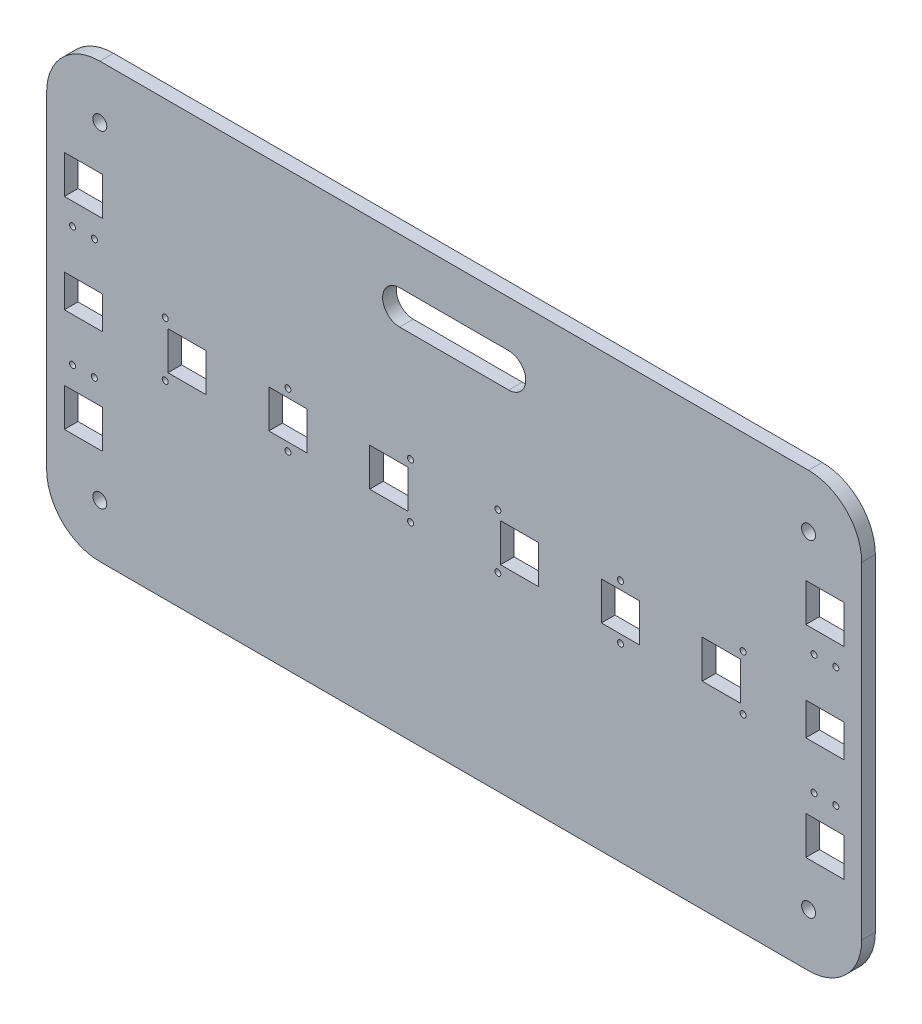
SolidWorks part; units mm, degrees
material "玻璃"
ref_plane "前视基准面" through (0, 0, 0) normal (0, 0, 1) x (1, 0, 0)
ref_plane "上视基准面" through (0, 0, 0) normal (0, 1, 0) x (1, 0, 0)
ref_plane "右视基准面" through (0, 0, 0) normal (1, 0, 0) x (0, 0, -1)
sketch "草图2" plane through (0, 0, 0) normal (0, 0, 1) x (1, 0, 0)
  line L0 (0, 1004.6496) -> (0, 0) construction
  line L10 (-68, -43) -> (-68, -57)
  line L11 (-31, -43) -> (-17, -43)
  line L19 (-22.1829, -50) -> (7.7078, -50) construction
  line L24 (31, -57) -> (17, -57)
  line L29 (17, -43) -> (17, -57)
  line L46 (129, -80) -> (143, -80)
  line L47 (-130, -130) -> (130, -130) construction
  line L48 (-150, -110) -> (-150, 10) construction
  line L49 (-130, 30) -> (130, 30) construction
  line L50 (150, -110) -> (150, 10) construction
  line L51 (0, 30) -> (0, 0) construction
  line L52 (-150, -50) -> (150, -50) construction
  line L53 (129, -6) -> (143, -6)
  line L58 (129, -6) -> (129, -20)
  line L59 (129, -20) -> (143, -20)
  line L60 (143, -6) -> (143, -20)
  line L65 (28.2222, 0) -> (37.5982, 0) construction
  line L66 (0, 0) -> (0, -130) construction
  line L71 (-130, 29.5) -> (130, 29.5)
  line L72 (-20, 12.5) -> (20, 12.5)
  line L73 (0, 0) -> (0, -1009.2088) construction
  line L74 (136, -20) -> (136, -6) construction
  line L75 (129, -13) -> (143, -13) construction
  line L76 (143, -94) -> (143, -80)
  line L77 (129, -94) -> (143, -94)
  line L78 (129, -94) -> (129, -80)
  line L79 (-129, -94) -> (-129, -80)
  line L80 (-129, -94) -> (-143, -94)
  line L81 (-143, -94) -> (-143, -80)
  line L82 (-129, -80) -> (-143, -80)
  line L83 (-129, -20) -> (-143, -20)
  line L84 (-143, -6) -> (-143, -20)
  line L85 (-129, -6) -> (-143, -6)
  line L86 (-129, -6) -> (-129, -20)
  line L87 (-31, -43) -> (-31, -57)
  line L88 (-31, -57) -> (-17, -57)
  line L89 (-17, -43) -> (-17, -57)
  line L90 (-24, -57) -> (-24, -43) construction
  line L91 (-31, -50) -> (-17, -50) construction
  line L92 (-68, -43) -> (-54, -43)
  line L93 (-54, -43) -> (-54, -57)
  line L94 (-68, -57) -> (-54, -57)
  line L95 (-105, -43) -> (-105, -57)
  line L96 (-105, -43) -> (-91, -43)
  line L97 (-91, -43) -> (-91, -57)
  line L98 (-105, -57) -> (-91, -57)
  line L99 (31, -43) -> (17, -43)
  line L100 (31, -43) -> (31, -57)
  line L101 (68, -43) -> (54, -43)
  line L102 (54, -43) -> (54, -57)
  line L103 (68, -57) -> (54, -57)
  line L104 (68, -43) -> (68, -57)
  line L105 (105, -43) -> (91, -43)
  line L106 (91, -43) -> (91, -57)
  line L107 (105, -57) -> (91, -57)
  line L108 (105, -43) -> (105, -57)
  line L109 (-31, -43) -> (-68, -43) construction
  line L110 (-61, -43) -> (-61, -57) construction
  line L112 (-111, -35) -> (-11, -35) construction
  line L113 (-111, -35) -> (-111, -65) construction
  line L114 (-111, -65) -> (-11, -65) construction
  line L115 (-11, -35) -> (-11, -65) construction
  line L116 (-61, -65) -> (-61, -35) construction
  line L117 (-111, -50) -> (-11, -50) construction
  line L121 (-106, -40) -> (-16, -40) construction
  line L122 (-16, -40) -> (-16, -60) construction
  line L123 (-106, -60) -> (-16, -60) construction
  line L124 (-106, -40) -> (-106, -60) construction
  line L125 (136, -20) -> (136, -42.3074) construction
  line L126 (-20, 12.5) -> (-20, 0) construction
  line L127 (128, -4) -> (144, -4) construction
  line L128 (128, -4) -> (128, -96) construction
  line L129 (128, -96) -> (144, -96) construction
  line L130 (144, -4) -> (144, -96) construction
  line L131 (136, -96) -> (136, -4) construction
  line L132 (128, -50) -> (144, -50) construction
  line L133 (132, -28) -> (140, -28) construction
  line L134 (132, -28) -> (132, -72) construction
  line L135 (132, -72) -> (140, -72) construction
  line L136 (140, -28) -> (140, -72) construction
  line L137 (136, -72) -> (136, -28) construction
  line L138 (132, -50) -> (140, -50) construction
  line L139 (-20, 0) -> (20, 0)
  line L140 (20, 12.5) -> (20, 0) construction
  line L141 (0, 0) -> (0, 12.5) construction
  line L142 (-20, 6.25) -> (20, 6.25) construction
  line L143 (149.5, -110) -> (149.5, 10)
  line L144 (-130, -129.5) -> (130, -129.5)
  line L145 (-149.5, -110) -> (-149.5, 10)
  line L146 (-129, -56) -> (-143, -56)
  line L147 (129, -44) -> (143, -44)
  line L148 (129, -44) -> (129, -56)
  line L149 (129, -56) -> (143, -56)
  line L150 (143, -44) -> (143, -56)
  line L151 (136, -56) -> (136, -44) construction
  line L152 (129, -50) -> (143, -50) construction
  line L153 (-143, -44) -> (-143, -56)
  line L154 (-129, -44) -> (-143, -44)
  line L155 (-129, -44) -> (-129, -56)
  arc A0 (130, 30) -> (150, 10) centre (130, 10) cw construction
  arc A1 (150, -110) -> (130, -130) centre (130, -110) cw construction
  arc A2 (-130, -130) -> (-150, -110) centre (-130, -110) cw construction
  arc A3 (-150, 10) -> (-130, 30) centre (-130, 10) cw construction
  circle A5 centre (130, -110) radius 2.55
  circle A6 centre (130, 10) radius 2.55
  circle A7 centre (-130, -110) radius 2.55
  circle A8 centre (-130, 10) radius 2.55
  circle A13 centre (-106, -40) radius 1.1
  circle A14 centre (-106, -60) radius 1.1
  circle A15 centre (-16, -40) radius 1.1
  circle A16 centre (-16, -60) radius 1.1
  circle A17 centre (-61, -60) radius 1.1
  circle A18 centre (-61, -40) radius 1.1
  circle A19 centre (16, -60) radius 1.1
  circle A20 centre (16, -40) radius 1.1
  circle A21 centre (61, -60) radius 1.1
  circle A22 centre (61, -40) radius 1.1
  circle A23 centre (106, -60) radius 1.1
  circle A24 centre (106, -40) radius 1.1
  circle A25 centre (140, -28) radius 1.1
  circle A26 centre (132, -28) radius 1.1
  circle A27 centre (132, -72) radius 1.1
  circle A28 centre (140, -72) radius 1.1
  circle A29 centre (-140, -72) radius 1.1
  circle A30 centre (-132, -72) radius 1.1
  circle A31 centre (-132, -28) radius 1.1
  circle A32 centre (-140, -28) radius 1.1
  arc A33 (-20, 12.5) -> (-20, 0) centre (-20, 6.25) ccw
  arc A34 (20, 0) -> (20, 12.5) centre (20, 6.25) ccw
  arc A35 (130, 29.5) -> (149.5, 10) centre (130, 10) cw
  arc A36 (149.5, -110) -> (130, -129.5) centre (130, -110) cw
  arc A37 (-130, -129.5) -> (-149.5, -110) centre (-130, -110) cw
  arc A38 (-149.5, 10) -> (-130, 29.5) centre (-130, 10) cw
  point P0 (0, 0)
  point P1 (0, 0)
  point P4 (-24, -50)
  point P36 (-61, -50)
  point P38 (0, -50)
  point P39 (-61, -50)
  point P40 (0, -50)
  point P41 (136, -13)
  point P51 (136, -50)
  point P53 (136, -50)
  point P54 (136, -50)
  point P61 (150, 30)
  point P64 (150, -130)
  point P70 (-150, 30)
  point P102 (-61, -40)
  point P103 (-61, -60)
  point P142 (136, -50)
  point P145 (0, 6.25)
  dimension "D15" = 20
  dimension "D16" = 5.1
  dimension "D17" = 5.1
  dimension "D18" = 5.1
  dimension "D19" = 5.1
  dimension "D20" = 30
  dimension "D25" = 2.2
  dimension "D26" = 2.2
  dimension "D27" = 2.2
  dimension "D28" = 2.2
  dimension "D29" = 2.2
  dimension "D30" = 2.2
  dimension "D35" = 2.2
  dimension "D36" = 2.2
  dimension "D37" = 2.2
  dimension "D38" = 2.2
  dimension "D3" = 14
  dimension "D4" = 14
  dimension "D5" = 17
  dimension "D6" = 40
  dimension "D7" = 12.5
  dimension "D8" = 3
  dimension "D9" = 37
  dimension "D10" = 300
  dimension "D11" = 160
  dimension "D12" = 14
  dimension "D13" = 14
  dimension "D14" = 7
  dimension "D21" = 100
  dimension "D22" = 50
  dimension "D23" = 30
  dimension "D24" = 5
  dimension "D31" = 92
  dimension "D32" = 16
  dimension "D33" = 8
  dimension "D34" = 44
  dimension "D39" = 0
  dimension "D41" = 14
  dimension "D42" = 12
  dimension "D40" = 0.5
extrude "凸台-拉伸1" add sketch "草图2" along normal blind 5
